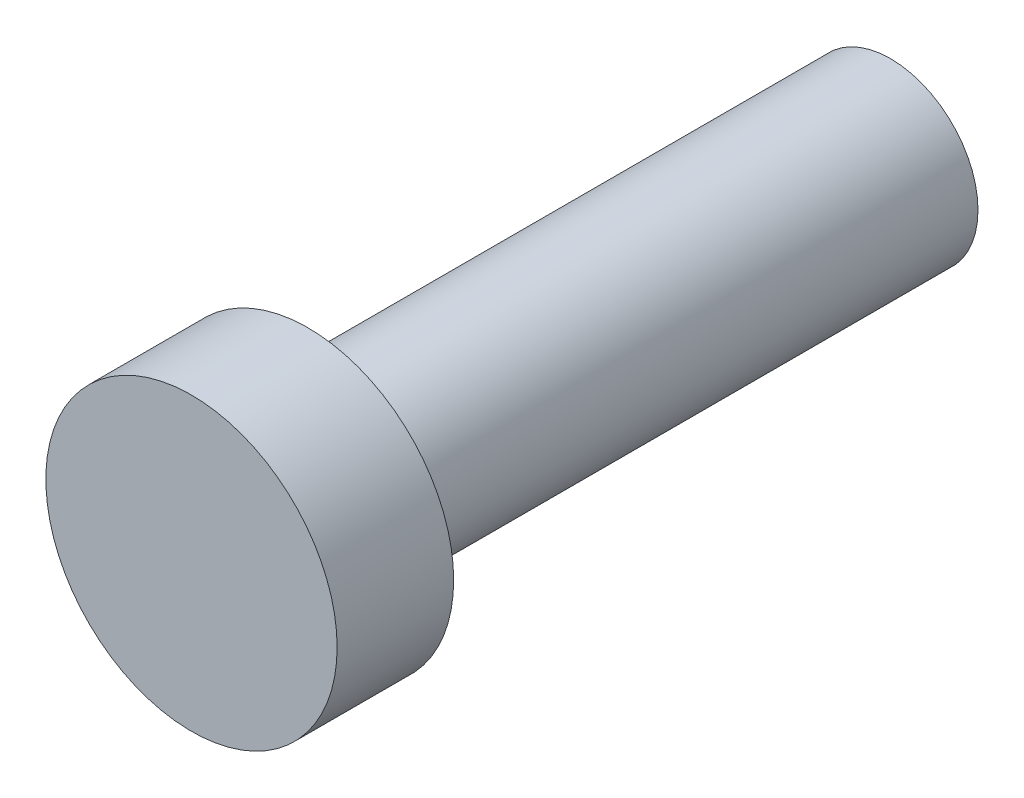
SolidWorks part; units mm, degrees
ref_plane "Plan de face" through (0, 0, 0) normal (0, 0, 1) x (1, 0, 0)
ref_plane "Plan de dessus" through (0, 0, 0) normal (0, 1, 0) x (1, 0, 0)
ref_plane "Plan de droite" through (0, 0, 0) normal (1, 0, 0) x (0, 0, -1)
sketch "Esquisse1" plane through (0, 0, 0) normal (0, 0, 1) x (1, 0, 0)
  circle A0 centre (0, 0) radius 1.5
  dimension "D1" = 3
extrude "Boss.-Extru.1" add sketch "Esquisse1" against normal blind 10
sketch "Esquisse2" plane through (0, 0, 0) normal (0, 0, 1) x (1, 0, 0)
  circle A0 centre (0, 0) radius 2.5
  dimension "D1" = 5
extrude "Boss.-Extru.2" add sketch "Esquisse2" along normal blind 2
